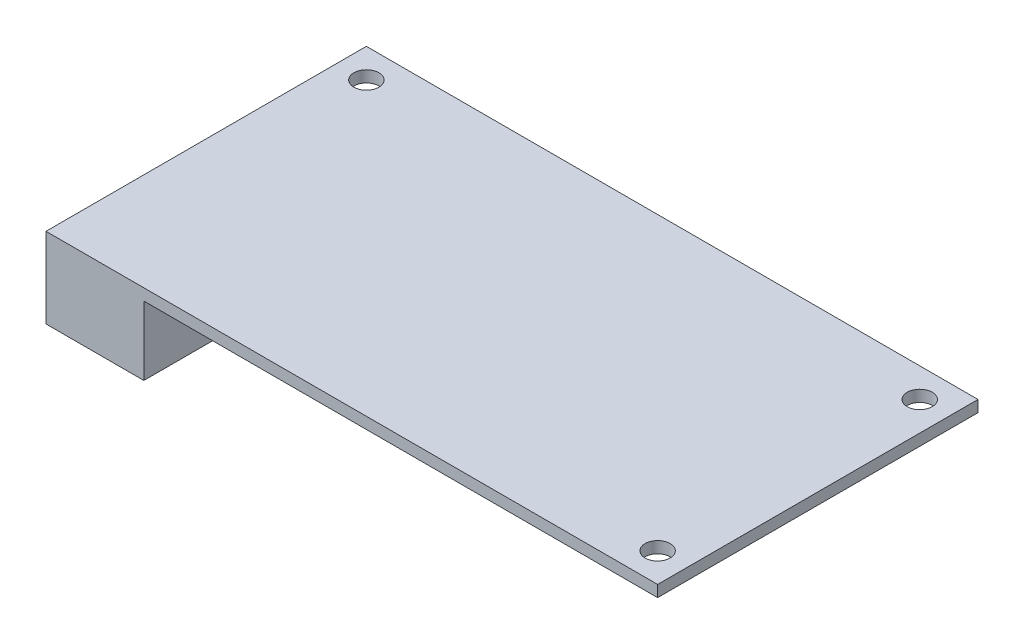
SolidWorks part; units mm, degrees
ref_plane "Front Plane" through (0, 0, 0) normal (0, 0, 1) x (1, 0, 0)
ref_plane "Top Plane" through (0, 0, 0) normal (0, 1, 0) x (1, 0, 0)
ref_plane "Right Plane" through (0, 0, 0) normal (1, 0, 0) x (0, 0, -1)
sketch "Sketch1" plane through (0, 0, 0) normal (0, 1, 0) x (1, 0, 0)
  line L1 (-26.67, -13.97) -> (26.67, -13.97)
  line L2 (-26.67, -13.97) -> (-26.67, 13.97)
  line L3 (-26.67, 13.97) -> (26.67, 13.97)
  line L4 (26.67, -13.97) -> (26.67, 13.97)
  line L5 (-26.67, -13.97) -> (26.67, 13.97) construction
  line L6 (-26.67, 13.97) -> (26.67, -13.97) construction
  line L7 (-24.13, -11.43) -> (24.13, -11.43) construction
  line L8 (-24.13, -11.43) -> (-24.13, 11.43) construction
  line L9 (-24.13, 11.43) -> (24.13, 11.43) construction
  line L10 (24.13, -11.43) -> (24.13, 11.43) construction
  line L11 (-24.13, -11.43) -> (24.13, 11.43) construction
  line L12 (-24.13, 11.43) -> (24.13, -11.43) construction
  circle A0 centre (-24.13, 11.43) radius 1.0922
  circle A1 centre (24.13, 11.43) radius 1.0922
  circle A2 centre (24.13, -11.43) radius 1.0922
  point P0 (0, 0)
  point P6 (0, 0)
  dimension "D5" = 2.1844
  dimension "D1" = 53.34
  dimension "D2" = 27.94
  dimension "D3" = 48.26
  dimension "D4" = 22.86
extrude "Boss-Extrude1" add sketch "Sketch1" along normal blind 1
sketch "Sketch2" plane through (0, 1, 0) normal (0, 1, 0) x (1, 0, 0)
  line L0 (-26.67, -13.97) -> (26.67, -13.97) construction
  line L5 (-26.67, 13.97) -> (-26.67, -13.97) construction
  line L6 (-26.67, 5.9135) -> (-18.1364, 5.9135)
  line L7 (-26.67, 5.9135) -> (-26.67, -13.97)
  line L8 (-26.67, -13.97) -> (-18.1364, -13.97)
  line L9 (-18.1364, 5.9135) -> (-18.1364, -13.97)
  line L10 (26.67, 13.97) -> (-26.67, 13.97) construction
  line L11 (-5.1818, 13.97) -> (5.0619, 13.97)
  line L12 (-5.1818, 13.97) -> (-5.1818, 6.4413)
  line L13 (-5.1818, 6.4413) -> (5.0619, 6.4413)
  line L14 (5.0619, 13.97) -> (5.0619, 6.4413)
extrude "Boss-Extrude2" add sketch "Sketch2" against normal blind 7
